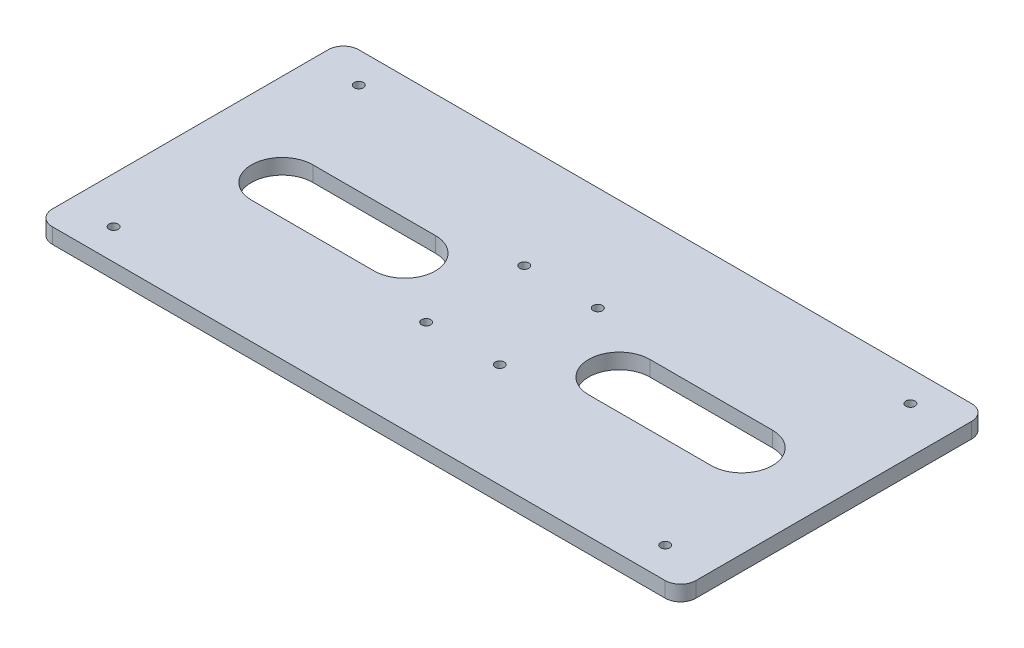
SolidWorks part; units mm, degrees
ref_plane "前视基准面" through (0, 0, 0) normal (0, 0, 1) x (1, 0, 0)
ref_plane "上视基准面" through (0, 0, 0) normal (0, 1, 0) x (1, 0, 0)
ref_plane "右视基准面" through (0, 0, 0) normal (1, 0, 0) x (0, 0, -1)
other "Configuration Table"
sketch "草图1" plane through (0, 0, 0) normal (0, 1, 0) x (1, 0, 0)
  line L1 (0, 0) -> (210, 0)
  line L2 (0, 0) -> (0, -100)
  line L3 (0, -100) -> (210, -100)
  line L4 (210, 0) -> (210, -100)
  dimension "D1" = 210
  dimension "D2" = 100
extrude "凸台-拉伸1" add sketch "草图1" along normal blind 5
sketch "草图2" plane through (0, 5, 0) normal (0, 1, 0) x (1, 0, 0)
  line L0 (0, -50) -> (210, -50) construction
  line L1 (0, 0) -> (0, -100) construction
  line L2 (210, -100) -> (210, 0) construction
  line L3 (105, 0) -> (105, -100) construction
  line L4 (210, 0) -> (0, 0) construction
  line L5 (0, -100) -> (210, -100) construction
  line L6 (30, -50) -> (70, -50) construction
  line L7 (30, -40) -> (70, -40)
  line L8 (30, -60) -> (70, -60)
  line L9 (140, -50) -> (180, -50) construction
  line L10 (140, -40) -> (180, -40)
  line L11 (140, -60) -> (180, -60)
  arc A0 (30, -40) -> (30, -60) centre (30, -50) ccw
  arc A1 (70, -60) -> (70, -40) centre (70, -50) ccw
  arc A2 (140, -40) -> (140, -60) centre (140, -50) ccw
  arc A3 (180, -60) -> (180, -40) centre (180, -50) ccw
  point P12 (105, -50)
  point P15 (50, -50)
  point P20 (160, -50)
  dimension "D3" = 10
  dimension "D1" = 35
  dimension "D2" = 40
  dimension "D4" = 35
extrude "切除-拉伸1" cut sketch "草图2" against normal blind 40
sketch "草图8" plane through (0, 5, 0) normal (0, 1, 0) x (1, 0, 0)
  line L0 (0, 0) -> (0, -100) construction
  line L1 (210, 0) -> (0, 0) construction
  line L2 (0, -50) -> (210, -50) construction
  line L3 (210, -100) -> (210, 0) construction
  line L4 (105, 0) -> (105, -100) construction
  line L5 (0, -100) -> (210, -100) construction
  circle A0 centre (15, -10) radius 1.5
  circle A1 centre (15, -90) radius 1.5
  circle A2 centre (195, -90) radius 1.5
  circle A3 centre (195, -10) radius 1.5
  dimension "D1" = 3
  dimension "D2" = 15
  dimension "D3" = 10
extrude "切除-拉伸7" cut sketch "草图8" against normal up to surface (5 mm away) up to face at (50, 0, 50)
fillet "圆角1" radius 5 4 edges at (210, 2.5, 0) (210, 2.5, 100) (0, 2.5, 100) (0, 2.5, 0)
sketch "草图9" plane through (0, 5, 0) normal (0, 1, 0) x (1, 0, 0)
  line L0 (105, 0) -> (105, -100) construction
  line L1 (205, 0) -> (5, 0) construction
  line L2 (5, -100) -> (205, -100) construction
  line L3 (0, -50) -> (210, -50) construction
  line L4 (0, -5) -> (0, -95) construction
  line L5 (210, -95) -> (210, -5) construction
  line L7 (120, -69) -> (90, -69) construction
  line L8 (120, -69) -> (120, -31) construction
  line L9 (120, -31) -> (90, -31) construction
  line L10 (90, -69) -> (90, -31) construction
  line L11 (120, -69) -> (90, -31) construction
  line L12 (120, -31) -> (90, -69) construction
  circle A0 centre (93, -34) radius 1.5
  circle A1 centre (117, -34) radius 1.5
  circle A2 centre (117, -66) radius 1.5
  circle A3 centre (93, -66) radius 1.5
  point P12 (105, -50)
  dimension "D3" = 3
  dimension "D1" = 30
  dimension "D2" = 38
  dimension "D4" = 3
  dimension "D5" = 3
extrude "切除-拉伸8" cut sketch "草图9" against normal through all
